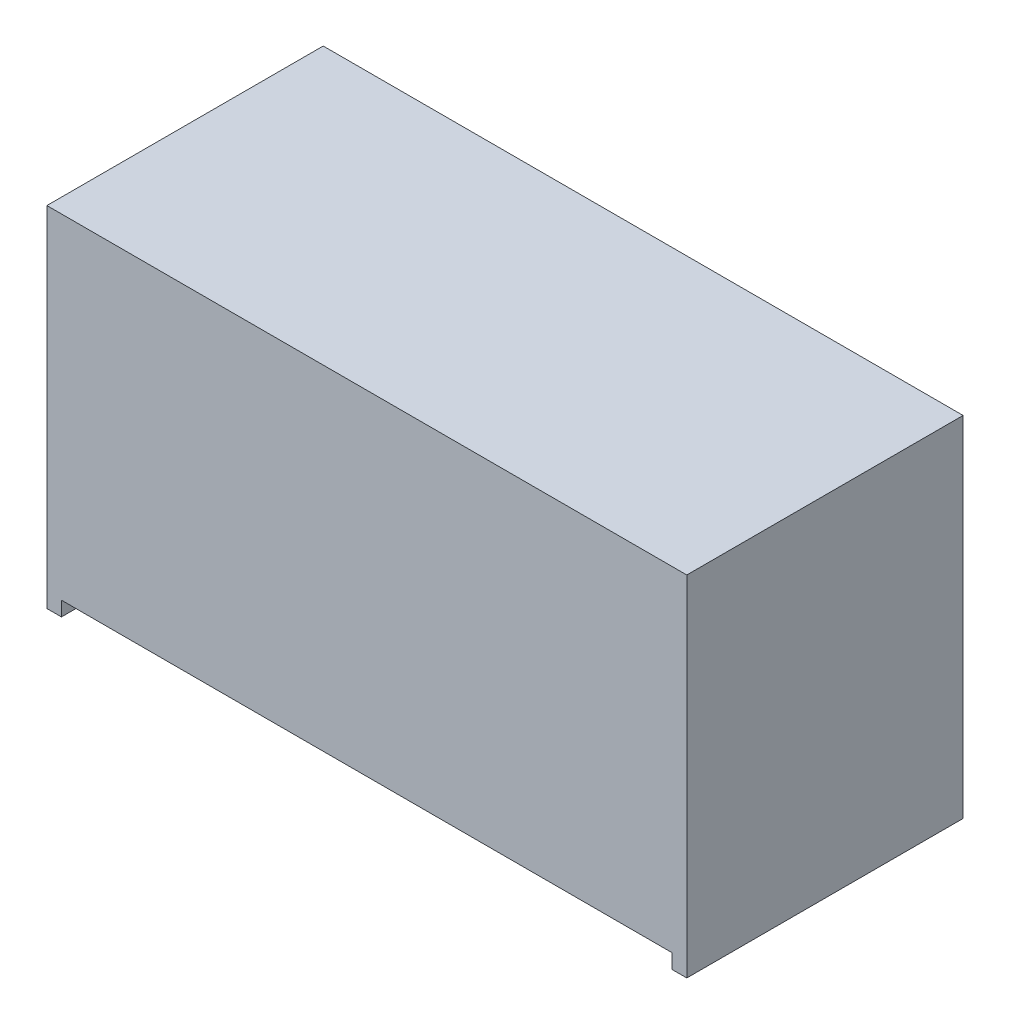
SolidWorks part; units mm, degrees
ref_plane "Front Plane" through (0, 0, 0) normal (0, 0, 1) x (1, 0, 0)
ref_plane "Top Plane" through (0, 0, 0) normal (0, 1, 0) x (1, 0, 0)
ref_plane "Right Plane" through (0, 0, 0) normal (1, 0, 0) x (0, 0, -1)
sketch "Sketch1" plane through (0, 0, 0) normal (0, 1, 0) x (1, 0, 0)
  line L1 (-11, 4.75) -> (11, 4.75)
  line L2 (-11, 4.75) -> (-11, -4.75)
  line L3 (-11, -4.75) -> (11, -4.75)
  line L4 (11, 4.75) -> (11, -4.75)
  line L5 (-11, 4.75) -> (11, -4.75) construction
  line L6 (-11, -4.75) -> (11, 4.75) construction
  point P0 (0, 0)
  dimension "D1" = 22
  dimension "D2" = 9.5
extrude "Boss-Extrude1" add sketch "Sketch1" along normal blind 12
sketch "Sketch2" plane through (0, 0, 4.75) normal (0, 0, 1) x (1, 0, 0)
  line L0 (-11, 12) -> (-11, 0) construction
  line L1 (-10.5, -1.3511) -> (10.5, -1.3511)
  line L2 (-10.5, -1.3511) -> (-10.5, 0.5)
  line L3 (-10.5, 0.5) -> (10.5, 0.5)
  line L4 (10.5, -1.3511) -> (10.5, 0.5)
  line L5 (11, 12) -> (11, 0) construction
  line L6 (-11, 0) -> (11, 0) construction
  dimension "D1" = 0.5
  dimension "D2" = 0.5
  dimension "D3" = 0.5
extrude "Cut-Extrude1" cut sketch "Sketch2" against normal up to next
